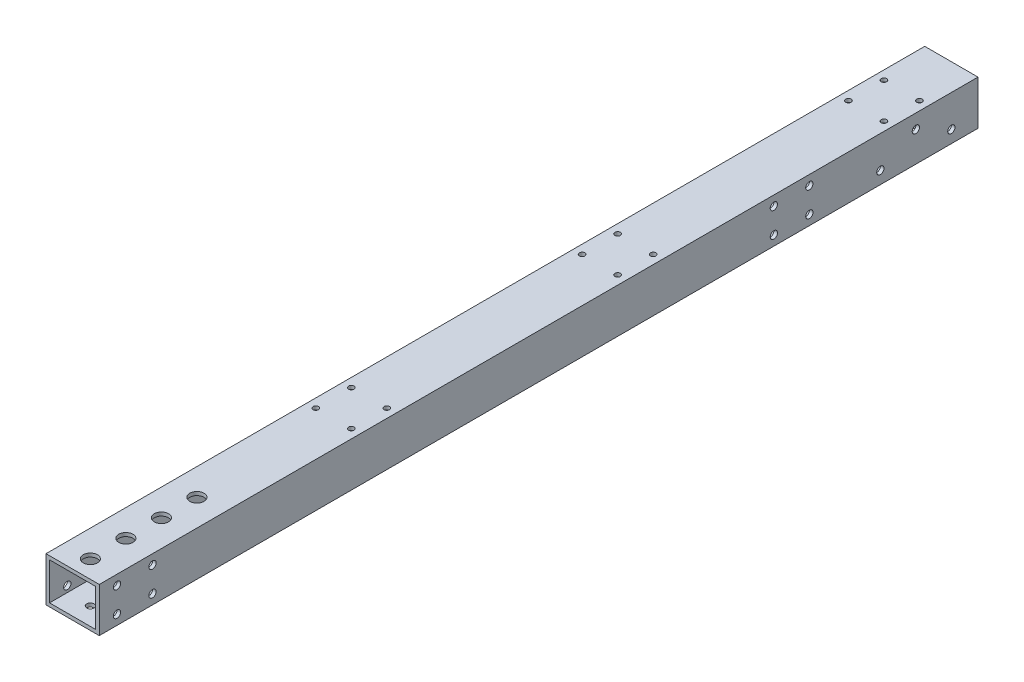
SolidWorks part; units mm, degrees
material "6063-T1"
ref_plane "前视基准面" through (0, 0, 0) normal (0, 0, 1) x (1, 0, 0)
ref_plane "上视基准面" through (0, 0, 0) normal (0, 1, 0) x (1, 0, 0)
ref_plane "右视基准面" through (0, 0, 0) normal (1, 0, 0) x (0, 0, -1)
other "Configuration Table"
sketch "草图1" plane through (0, 0, 0) normal (0, 0, 1) x (1, 0, 0)
  line L1 (-15, 12.5) -> (15, 12.5)
  line L2 (-15, 12.5) -> (-15, -12.5)
  line L3 (-15, -12.5) -> (15, -12.5)
  line L4 (15, 12.5) -> (15, -12.5)
  line L7 (-13, 10.5) -> (13, 10.5)
  line L8 (-13, 10.5) -> (-13, -10.5)
  line L9 (-13, -10.5) -> (13, -10.5)
  line L10 (13, 10.5) -> (13, -10.5)
  line L11 (-13, 10.5) -> (13, -10.5) construction
  line L12 (-13, -10.5) -> (13, 10.5) construction
  point P0 (0, 0)
  point P6 (0, 0)
  dimension "D1" = 30
  dimension "D2" = 25
  dimension "D3" = 2
  dimension "D4" = 2
  dimension "D5" = 2
  dimension "D6" = 2
extrude "凸台-拉伸1" add sketch "草图1" along normal blind 510
sketch "草图4" plane through (0, -12.5, 0) normal (0, -1, 0) x (1, 0, 0)
  line L0 (0, 40) -> (0, 60) construction
  line L1 (-7.5, 40) -> (-7.5, 60)
  line L2 (7.5, 40) -> (7.5, 60)
  line L3 (-15, 0) -> (15, 0) construction
  line L4 (0, 190) -> (0, 210) construction
  line L5 (-7.5, 190) -> (-7.5, 210)
  line L6 (7.5, 190) -> (7.5, 210)
  line L7 (0, 340) -> (0, 360) construction
  line L8 (-7.5, 340) -> (-7.5, 360)
  line L9 (7.5, 340) -> (7.5, 360)
  line L10 (0, 40) -> (0, 190) construction
  arc A0 (-7.5, 40) -> (7.5, 40) centre (0, 40) ccw
  arc A1 (7.5, 60) -> (-7.5, 60) centre (0, 60) ccw
  arc A2 (-7.5, 190) -> (7.5, 190) centre (0, 190) ccw
  arc A3 (7.5, 210) -> (-7.5, 210) centre (0, 210) ccw
  arc A4 (-7.5, 340) -> (7.5, 340) centre (0, 340) ccw
  arc A5 (7.5, 360) -> (-7.5, 360) centre (0, 360) ccw
  point P3 (0, 50)
  point P14 (0, 200)
  point P21 (0, 350)
  dimension "D1" = 40
  dimension "D2" = 15
  dimension "D3" = 20
  dimension "D5" = 150
  dimension "D4" = 3
extrude "切除-拉伸4" cut sketch "草图4" against normal up to next
sketch "草图5" plane through (0, 12.5, 0) normal (0, 1, 0) x (1, 0, 0)
  line L0 (15, 0) -> (-15, 0) construction
  line L5 (0, 0) -> (0, -20.1517) construction
  circle A0 centre (-10, -43) radius 1.55
  circle A1 centre (10, -43) radius 1.55
  circle A2 centre (-10, -63) radius 1.55
  circle A3 centre (10, -63) radius 1.55
  circle A4 centre (-10, -193) radius 1.55
  circle A5 centre (-10, -213) radius 1.55
  circle A6 centre (10, -193) radius 1.55
  circle A7 centre (10, -213) radius 1.55
  circle A8 centre (-10, -343) radius 1.55
  circle A9 centre (-10, -363) radius 1.55
  circle A10 centre (10, -343) radius 1.55
  circle A11 centre (10, -363) radius 1.55
  dimension "D1" = 3.1
  dimension "D6" = 150
  dimension "D7" = 150
  dimension "D2" = 20
  dimension "D3" = 20
  dimension "D4" = 43
  dimension "D5" = 3
sketch "草图7" plane through (15, 0, 0) normal (1, 0, 0) x (0, 0, -1)
  line L0 (0, -12.5) -> (0, 12.5) construction
  line L2 (-510, -12.5) -> (0, -12.5) construction
  line L3 (-510, 12.5) -> (0, 12.5) construction
  circle A0 centre (-30, -5.5) radius 2.05
  circle A1 centre (-50, 4.5) radius 2.05
  circle A2 centre (-70, -5.5) radius 2.05
  dimension "D1" = 4.1
  dimension "D2" = 30
  dimension "D3" = 7
  dimension "D4" = 8
  dimension "D5" = 20
  dimension "D6" = 20
extrude "切除-拉伸7" cut sketch "草图7" against normal through all
sketch "草图9" plane through (0, -12.5, 0) normal (0, -1, 0) x (1, 0, 0)
  line L1 (0, 430) -> (9.292, 430) construction
  line L2 (0, 470) -> (9.6668, 470) construction
  circle A0 centre (0, 480) radius 2.05
  circle A1 centre (0, 500) radius 2.05
  circle A2 centre (0, 440) radius 2.05
  circle A3 centre (0, 460) radius 2.05
  dimension "D1" = 20
  dimension "D2" = 4.1
extrude "切除-拉伸9" cut sketch "草图9" against normal blind 10
sketch "草图10" plane through (0, 12.5, 0) normal (0, 1, 0) x (1, 0, 0)
  line L2 (0, -470) -> (-5.6573, -470) construction
  line L3 (0, -430) -> (-6.775, -430) construction
  circle A0 centre (0, -500) radius 4
  circle A1 centre (0, -480) radius 4
  circle A2 centre (0, -460) radius 4
  circle A3 centre (0, -440) radius 4
  dimension "D1" = 8
  dimension "D2" = 20
extrude "切除-拉伸10" cut sketch "草图10" against normal blind 10
sketch "草图11" plane through (-15, 0, 0) normal (-1, 0, 0) x (0, 0, 1)
  line L0 (0, 0) -> (27.3376, 0) construction
  line L1 (0, 12.5) -> (0, -12.5) construction
  line L2 (510, 0) -> (502.3475, 0) construction
  line L3 (510, 12.5) -> (510, -12.5) construction
  circle A0 centre (480, 7) radius 2.05
  circle A1 centre (500, 7) radius 2.05
  circle A2 centre (480, -7) radius 2.05
  circle A3 centre (500, -7) radius 2.05
  circle A4 centre (110, 7) radius 2.05
  circle A5 centre (130, 7) radius 2.05
  circle A6 centre (110, -7) radius 2.05
  circle A7 centre (130, -7) radius 2.05
  dimension "D1" = 4.1
  dimension "D2" = 14
  dimension "D4" = 110
  dimension "D5" = 4.1
  dimension "D7" = 14
  dimension "D8" = 10
  dimension "D3" = 20
  dimension "D6" = 20
extrude "切除-拉伸11" cut sketch "草图11" against normal blind 52
sketch "草图12" plane through (-15, 0, 0) normal (-1, 0, 0) x (0, 0, 1)
  line L0 (510, -12.5) -> (0, -12.5) construction
  line L1 (0, 12.5) -> (15, 12.5)
  line L2 (0, 12.5) -> (0, -12.5)
  line L3 (0, -12.5) -> (15, -12.5)
  line L4 (15, 12.5) -> (15, -12.5)
  dimension "D1" = 15
extrude "切除-拉伸12" cut sketch "草图12" against normal through all
extrude "切除-拉伸13" cut sketch "草图5" against normal up to next
